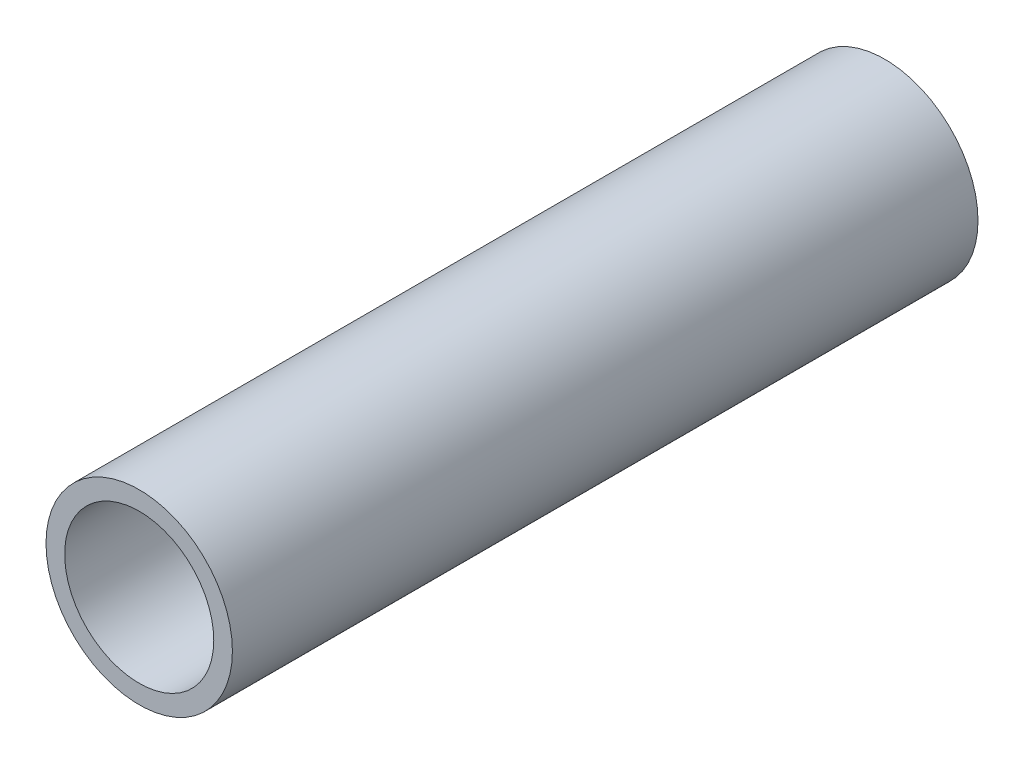
SolidWorks part; units mm, degrees
material "Thornel VCB-20 ｶｰﾎﾞﾝ ｸﾛｽ"
ref_plane "正面" through (0, 0, 0) normal (0, 0, 1) x (1, 0, 0)
ref_plane "平面" through (0, 0, 0) normal (0, 1, 0) x (1, 0, 0)
ref_plane "右側面" through (0, 0, 0) normal (1, 0, 0) x (0, 0, -1)
sketch "ｽｹｯﾁ1" plane through (0, 0, 0) normal (0, 0, 1) x (1, 0, 0)
  circle A0 centre (0, 0) radius 5
  circle A1 centre (0, 0) radius 4
  dimension "D1" = 10
  dimension "D2" = 8
extrude "ﾎﾞｽ - 押し出し1" add sketch "ｽｹｯﾁ1" along normal blind 40
sketch "ｽｹｯﾁ2" plane through (0, 0, 0) normal (0, 1, 0) x (1, 0, 0)
  line L0 (0, 0) -> (0, -40) construction
  line L1 (-4, -40) -> (4, -40) construction
sketch "ｽｹｯﾁ3" plane through (0, 0, 40) normal (0, 0, 1) x (1, 0, 0)
  line L0 (-5, 0) -> (5, 0) construction
  line L1 (0, 5) -> (0, -5) construction
  circle A0 centre (0, 0) radius 5 construction
  point P5 (0, 0)
  point P12 (0, 0)
  point P13 (0, 0)
sketch "ｽｹｯﾁ4" plane through (0, 0, 0) normal (0, 0, -1) x (-1, 0, 0)
  line L0 (0, -5) -> (0, 5) construction
  line L2 (5, 0) -> (-5, 0) construction
  point P4 (0, 0)
  point P9 (0, 0)
